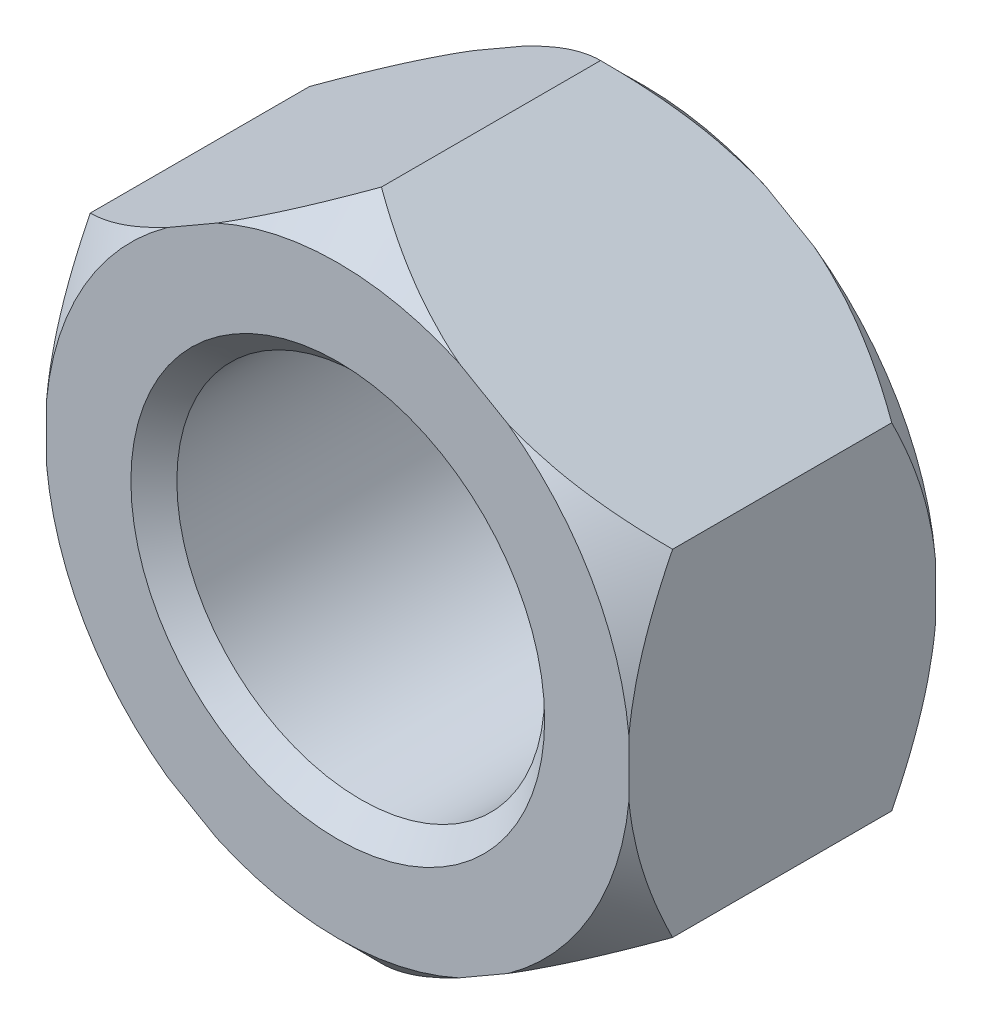
SolidWorks part; units mm, degrees
ref_plane "Спереди" through (0, 0, 0) normal (0, 0, 1) x (1, 0, 0)
ref_plane "Сверху" through (0, 0, 0) normal (0, 1, 0) x (1, 0, 0)
ref_plane "Справа" through (0, 0, 0) normal (1, 0, 0) x (0, 0, -1)
sketch "Эскиз1" plane through (0, 0, 0) normal (0, 0, 1) x (1, 0, 0)
  line L0 (0, 3.7738) -> (0, -4.1898) construction
  line L1 (-3.4469, 0) -> (3.2389, 0) construction
  line L3 (0, 10.9697) -> (-9.5, 5.4848)
  line L4 (-9.5, 5.4848) -> (-9.5, -5.4848)
  line L5 (-9.5, -5.4848) -> (0, -10.9697)
  line L6 (0, -10.9697) -> (9.5, -5.4848)
  line L7 (9.5, -5.4848) -> (9.5, 5.4848)
  line L8 (9.5, 5.4848) -> (0, 10.9697)
  circle A0 centre (0, 0) radius 9.5 construction
extrude "Вытянуть1" add sketch "Эскиз1" along normal blind 10
sketch "Эскиз2" plane through (0, 0, 0) normal (0, 0, -1) x (-1, 0, 0)
  circle A0 centre (0, 0) radius 6
ref_axis "Ось4" through (0, 0, 2.6338) along (0, 0, -1)
sketch "Эскиз15" plane through (0, 0, 0) normal (1, 0, 0) x (0, 0, -1)
  line L0 (-10, 10.9697) -> (-10, 9.5447)
  line L1 (-10, 5.4848) -> (-10, 10.9697) construction
  line L2 (-10, 9.5447) -> (-8.575, 10.9697)
  line L3 (-10, 10.9697) -> (0, 10.9697) construction
  line L4 (-8.575, 10.9697) -> (-10, 10.9697)
  line L5 (-1.425, 10.9697) -> (0, 10.9697)
  line L6 (0, 10.9697) -> (0, 9.5447)
  line L7 (0, 9.5447) -> (-1.425, 10.9697)
revolve "Вырез-Повернуть1" cut sketch "Эскиз15" angle 360 about axis through (0, 0, 2.6338) along (0, 0, -1)
ref_plane "Плоскость1" through (9.5, 0.9222, 10) normal (-0.0966, 0.9953, 0) x (-0.9953, -0.0966, 0)
extrude "Вырез-Вытянуть1" cut sketch "Эскиз2" against normal through all
chamfer "Фаска1" distance 0.75 angle 45 2 edges at (-6, 0, 0) (-6, 0, 10)
